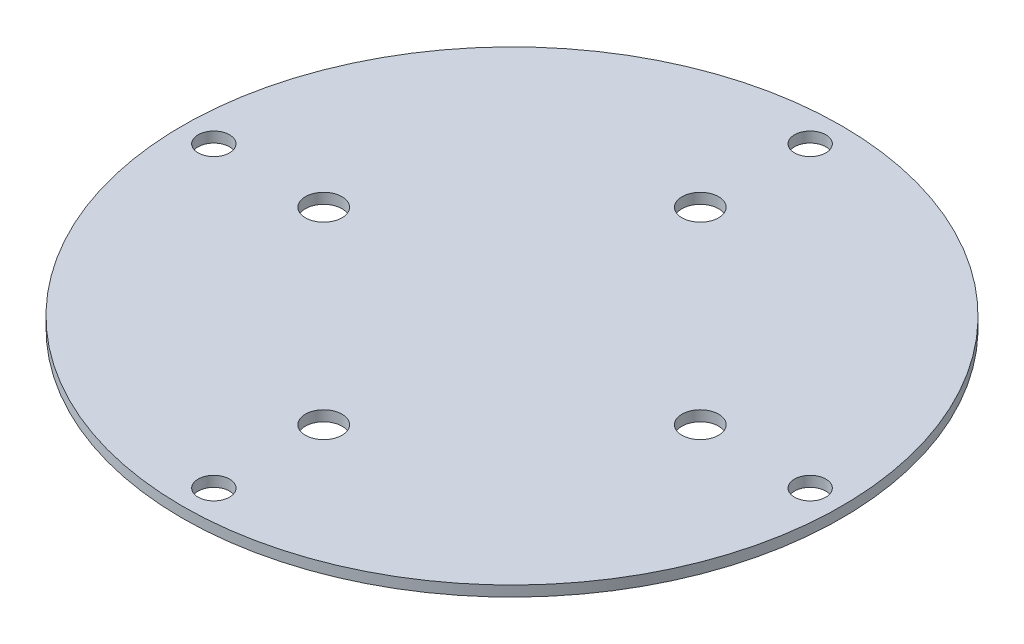
SolidWorks part; units mm, degrees
ref_plane "Front Plane" through (0, 0, 0) normal (0, 0, 1) x (1, 0, 0)
ref_plane "Top Plane" through (0, 0, 0) normal (0, 1, 0) x (1, 0, 0)
ref_plane "Right Plane" through (0, 0, 0) normal (1, 0, 0) x (0, 0, -1)
sketch "Sketch1" plane through (0, 0, 0) normal (0, 1, 0) x (1, 0, 0)
  line L0 (0, 0) -> (-10.6066, 10.6066)
  circle A0 centre (0, 0) radius 18
  circle A1 centre (0, 0) radius 15
  circle A2 centre (-18, 0) radius 1.75
  circle A7 centre (0, 18) radius 1.75
  circle A8 centre (18, 0) radius 1.75
  circle A9 centre (0, -18) radius 1.75
  circle A10 centre (0, 0) radius 22.5
  circle A11 centre (0, 0) radius 28.5
  circle A12 centre (28.5, 0) radius 1.5
  circle A13 centre (0, -28.5) radius 1.5
  circle A14 centre (-28.5, 0) radius 1.5
  circle A15 centre (0, 28.5) radius 1.5
  circle A16 centre (0, 0) radius 31.5
  point P17 (0, 0)
  point P24 (0, 0)
  point P28 (0, 0)
  dimension "D1" = 36
  dimension "D2" = 30
  dimension "D3" = 3.5
  dimension "D4" = 57
  dimension "D7" = 45
  dimension "D5" = 4
  dimension "D8" = 63
  dimension "D6" = 4
extrude "Boss-Extrude1" add sketch "Sketch1" along normal blind 1
